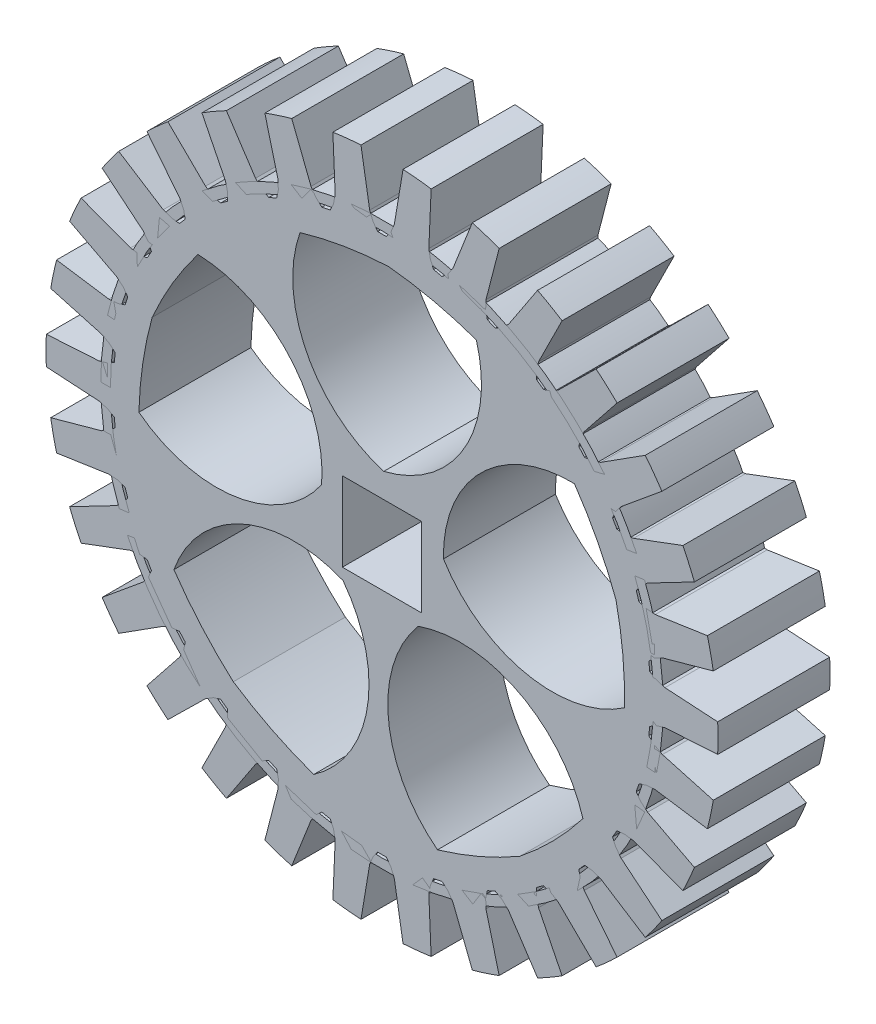
SolidWorks part; units mm, degrees
ref_plane "Front Plane" through (0, 0, 0) normal (0, 0, 1) x (1, 0, 0)
ref_plane "Top Plane" through (0, 0, 0) normal (0, 1, 0) x (1, 0, 0)
ref_plane "Right Plane" through (0, 0, 0) normal (1, 0, 0) x (0, 0, -1)
sketch "Sketch1" plane through (0, 0, 0) normal (0, 0, 1) x (1, 0, 0)
  line L1 (3.5355, -3.5355) -> (-3.5355, -3.5355)
  line L2 (3.5355, -3.5355) -> (3.5355, 3.5355)
  line L3 (3.5355, 3.5355) -> (-3.5355, 3.5355)
  line L4 (-3.5355, -3.5355) -> (-3.5355, 3.5355)
  line L5 (3.5355, -3.5355) -> (-3.5355, 3.5355) construction
  line L6 (3.5355, 3.5355) -> (-3.5355, -3.5355) construction
  circle A0 centre (0, 0) radius 30
  circle A1 centre (0, 0) radius 5 construction
  dimension "D1" = 60
  dimension "D2" = 10
extrude "Boss-Extrude1" add sketch "Sketch1" along normal blind 10
sketch "Sketch2" plane through (0, 0, 0) normal (0, 0, 1) x (1, 0, 0)
  line L0 (0, 0) -> (0, 31.7783) construction
  line L1 (0, 23.9952) -> (-0.3836, 23.9952)
  line L2 (-0.3836, 23.9952) -> (-0.7932, 24.5414)
  line L3 (-0.7932, 24.5414) -> (-1.1004, 25.2924)
  line L4 (-1.1004, 25.2924) -> (-1.8781, 29.9412)
  line L5 (-1.8781, 29.9412) -> (-2.7048, 31.2663)
  line L6 (-2.7048, 31.2663) -> (0, 31.7783)
  line L7 (2.7048, 31.2663) -> (0, 31.7783)
  line L8 (1.8781, 29.9412) -> (2.7048, 31.2663)
  line L9 (1.1004, 25.2924) -> (1.8781, 29.9412)
  line L10 (0.7932, 24.5414) -> (1.1004, 25.2924)
  line L11 (0.3836, 23.9952) -> (0.7932, 24.5414)
  line L12 (0, 23.9952) -> (0.3836, 23.9952)
  circle A22 centre (0, 0) radius 30 construction
  point P15 (-0.9653, 18.1566)
  point P16 (0.1037, 17.7857)
  point P17 (0.7146, 17.1749)
  point P18 (0, 0)
  point P19 (0, 0)
  point P20 (0, 0)
  point P21 (-1.3116, 19.3395)
  point P22 (-0.6868, 18.5174)
  point P23 (0, 17.7281)
  point P24 (-2.4954, 21.2467)
  point P25 (-3.7081, 22.1923)
  point P28 (-2.9887, 21.888)
  point P29 (-1.1323, 21.9535)
  point P30 (-1.4086, 22.4559)
  point P31 (-0.8269, 21.0772)
  point P32 (-0.4684, 20.7187)
  point P33 (-0.2161, 20.4266)
  point P34 (0, 20.3336)
  point P35 (-1.1004, 25.2924)
  point P36 (-0.7932, 24.5414)
  point P37 (0, 23.9952)
  point P38 (-0.3836, 23.9952)
  point P39 (-2.7048, 31.2663)
  point P40 (0, 31.7783)
extrude "Cut-Extrude1" cut sketch "Sketch2" along normal through all
pattern_circular "CirPattern1" count 30 over 360 about axis through (0, 0, 0) along (0, 0, 1) of "Cut-Extrude1"
sketch "Sketch3" plane through (0, 0, 0) normal (0, 0, 1) x (1, 0, 0)
  circle A0 centre (0, 0) radius 29.75
  dimension "D1" = 59.5
sketch "Sketch4" plane through (0, 0, 0) normal (0, 0, 1) x (1, 0, 0)
  line L0 (0, 0) -> (0.5934, 21.7714) construction
  arc A0 (0.1559, 5.7183) -> (-7.3195, 20.4479) centre (3.445, 16.6492) cw
  arc A1 (0.5934, 21.7714) -> (-7.3195, 20.4479) centre (2.0438, -11.2177) ccw
  arc A2 (0.5934, 21.7714) -> (8.4225, 20.0188) centre (-2.6519, -11.0897) cw
  arc A3 (0.1559, 5.7183) -> (8.4225, 20.0188) centre (-2.5329, 16.8121) ccw
  point P10 (-7.3195, 20.4479)
extrude "Cut-Extrude2" cut sketch "Sketch4" along normal through all both
sketch "Sketch5" plane through (0, 0, 0) normal (0, 0, 1) x (1, 0, 0)
  line L0 (3.5355, -3.5355) -> (-3.5355, 3.5355) construction
  circle A0 centre (0, 0) radius 25.1098
  circle A1 centre (0, 0) radius 24.2496
extrude "Boss-Extrude2" add sketch "Sketch5" along normal blind 10 separate body
pattern_circular "CirPattern2" count 5 over 360 about axis through (0, 0, 0) along (0, 0, 1) of "Cut-Extrude2"
